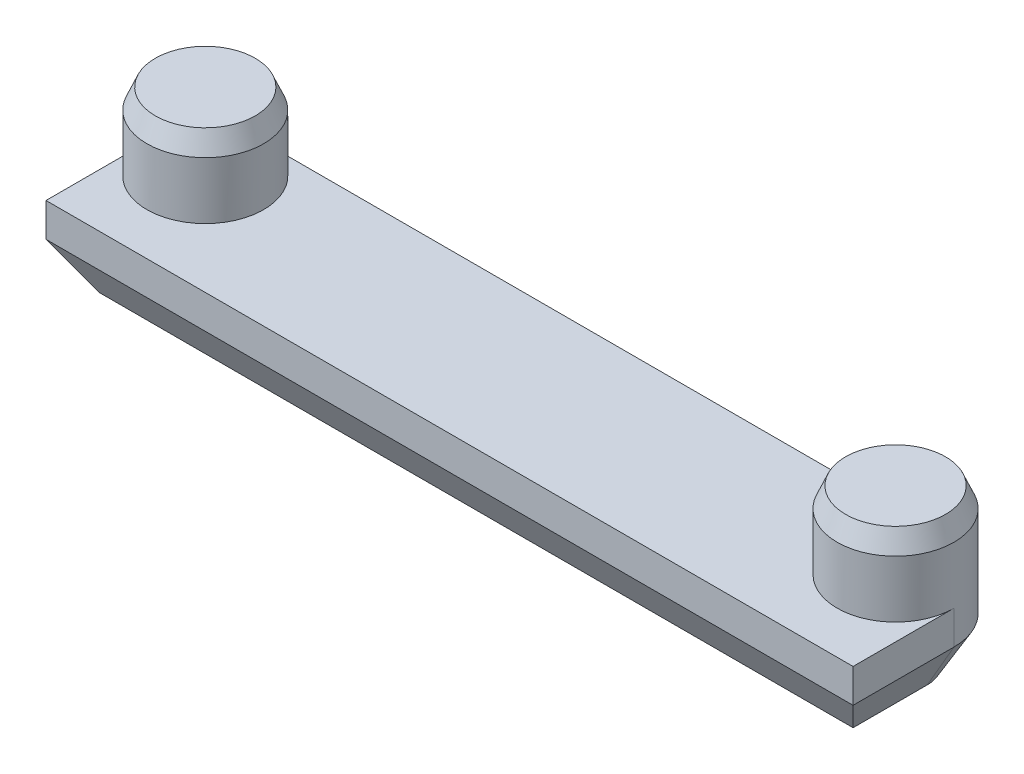
SolidWorks part; units mm, degrees
ref_plane "Front Plane" through (0, 0, 0) normal (0, 0, 1) x (1, 0, 0)
ref_plane "Top Plane" through (0, 0, 0) normal (0, 1, 0) x (1, 0, 0)
ref_plane "Right Plane" through (0, 0, 0) normal (1, 0, 0) x (0, 0, -1)
sketch "Sketch1" plane through (0, 0, 0) normal (0, 1, 0) x (1, 0, 0)
  line L1 (0, 0) -> (30.4, 0)
  line L2 (0, 0) -> (0, 6)
  line L3 (0, 6) -> (30.4, 6)
  line L4 (30.4, 0) -> (30.4, 6)
  dimension "D1" = 30.4
  dimension "D2" = 6
extrude "Boss-Extrude1" add sketch "Sketch1" along normal blind 3
sketch "Sketch2" plane through (0, 3, 0) normal (0, 1, 0) x (1, 0, 0)
  line L0 (30.4, 6) -> (0, 6) construction
  line L1 (0, 6) -> (0, 0) construction
  line L2 (30.4, 0) -> (30.4, 6) construction
  circle A0 centre (2.2, 3.8) radius 2.2
  circle A1 centre (28.2, 3.8) radius 2.2
  dimension "D1" = 4.4
extrude "Boss-Extrude2" add sketch "Sketch2" along normal blind 2.9
chamfer "Chamfer1" distance 0.75 angle 23 2 edges at (28.2, 5.9, -1.6) (2.2, 5.9, -1.6)
sketch "Sketch3" plane through (0, 3, 0) normal (0, 1, 0) x (1, 0, 0)
  line L0 (30.4, 3.8) -> (30.4, 6) construction
  line L1 (30.4, 6) -> (28.2, 6) construction
  line L2 (2.2, 6) -> (0, 6) construction
  line L3 (0, 6) -> (0, 3.8) construction
  line L4 (30.4, 3.8) -> (30.4, 6)
  line L5 (30.4, 6) -> (28.2, 6)
  line L6 (2.2, 6) -> (0, 6)
  line L7 (0, 6) -> (0, 3.8)
  arc A0 (30.4, 3.8) -> (28.2, 6) centre (28.2, 3.8) ccw construction
  arc A1 (2.2, 6) -> (0, 3.8) centre (2.2, 3.8) ccw construction
  arc A2 (30.4, 3.8) -> (28.2, 6) centre (28.2, 3.8) ccw
  arc A3 (2.2, 6) -> (0, 3.8) centre (2.2, 3.8) ccw
extrude "Cut-Extrude1" cut sketch "Sketch3" against normal blind 3
chamfer "Chamfer2" distance 1 angle 60 6 edges at (30.4, 0, -1.9) (0, 0, -1.9) (29.7556, 0, -5.3556) (0.6444, 0, -5.3556) (15.2, 0, -6) (15.2, 0, 0)
